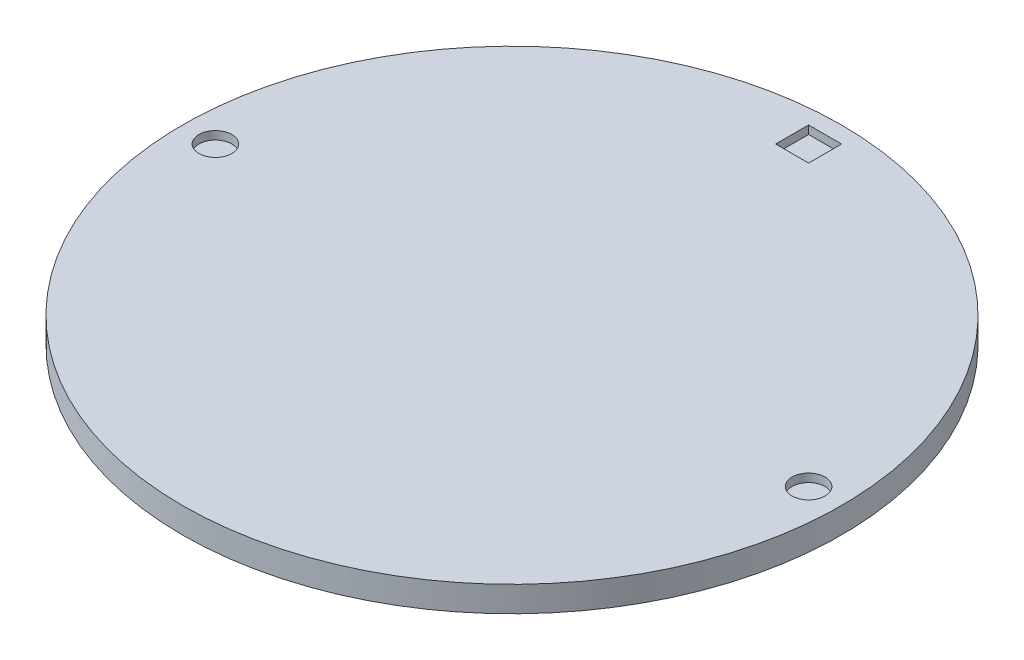
SolidWorks part; units mm, degrees
ref_plane "Front Plane" through (0, 0, 0) normal (0, 0, 1) x (1, 0, 0)
ref_plane "Top Plane" through (0, 0, 0) normal (0, 1, 0) x (1, 0, 0)
ref_plane "Right Plane" through (0, 0, 0) normal (1, 0, 0) x (0, 0, -1)
sketch "Sketch1" plane through (0, 0, 0) normal (0, 1, 0) x (1, 0, 0)
  line L0 (0, 0) -> (0, 360)
  line L1 (0, 0) -> (360, 0)
  line L2 (20, 380) -> (-20, 380)
  line L3 (20, 380) -> (20, 340)
  line L4 (20, 340) -> (-20, 340)
  line L5 (-20, 380) -> (-20, 340)
  line L6 (20, 380) -> (-20, 340) construction
  line L7 (20, 340) -> (-20, 380) construction
  circle A0 centre (0, 0) radius 400
  circle A1 centre (360, 0) radius 20
extrude "Boss-Extrude1" add sketch "Sketch1" against normal blind 30 and the other way blind 1 contours A0
sketch "Sketch2" plane through (0, 1, 0) normal (0, 1, 0) x (1, 0, 0)
  line L0 (0, 0) -> (360, 0)
  line L1 (0, 0) -> (0, 360)
  line L2 (0, 0) -> (-360, 0)
  line L4 (20, 380) -> (-20, 380)
  line L5 (20, 380) -> (20, 340)
  line L6 (20, 340) -> (-20, 340)
  line L7 (-20, 380) -> (-20, 340)
  line L8 (20, 380) -> (-20, 340) construction
  line L9 (20, 340) -> (-20, 380) construction
  circle A0 centre (-360, 0) radius 20
  circle A1 centre (360, 0) radius 20
extrude "Cut-Extrude1" cut sketch "Sketch2" against normal blind 10 contours A0 | A1 | L4 L7 L6 L5
